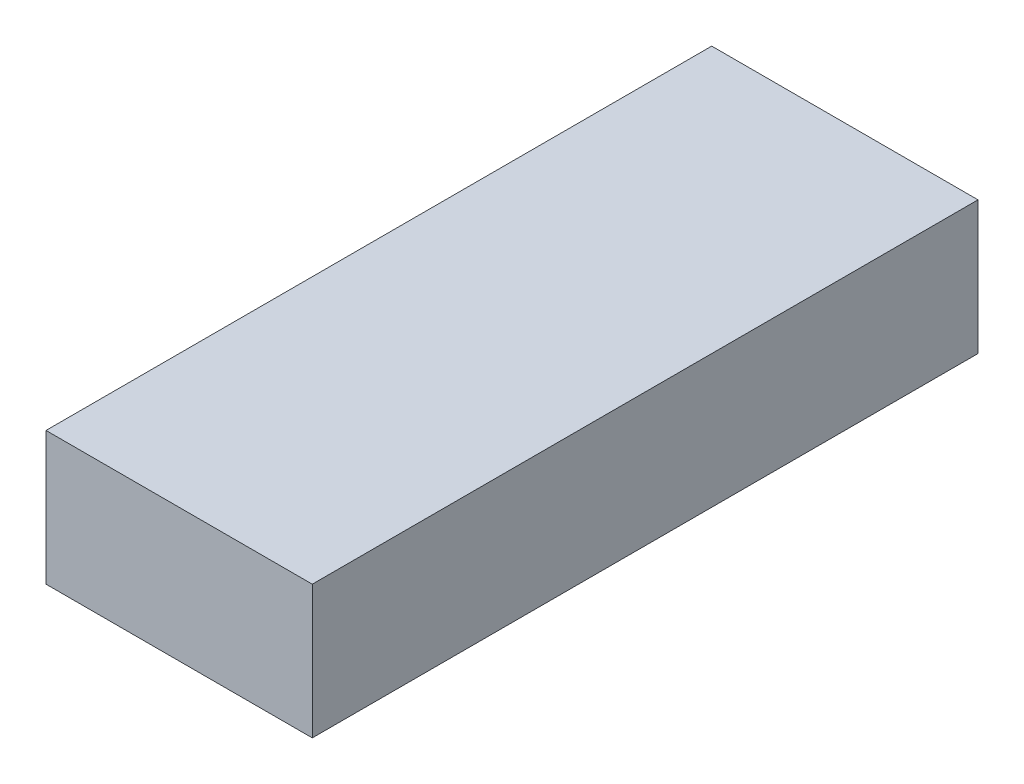
SolidWorks part; units mm, degrees
ref_plane "Front Plane" through (0, 0, 0) normal (0, 0, 1) x (1, 0, 0)
ref_plane "Top Plane" through (0, 0, 0) normal (0, 1, 0) x (1, 0, 0)
ref_plane "Right Plane" through (0, 0, 0) normal (1, 0, 0) x (0, 0, -1)
sketch "Sketch1" plane through (0, 0, 0) normal (0, 0, 1) x (1, 0, 0)
  line L1 (3, -1.5) -> (-3, -1.5)
  line L2 (3, -1.5) -> (3, 1.5)
  line L3 (3, 1.5) -> (-3, 1.5)
  line L4 (-3, -1.5) -> (-3, 1.5)
  line L5 (0, 1.5) -> (0, -1.5) construction
  line L6 (3, 0) -> (-3, 0) construction
  point P0 (0, 0)
  dimension "D1" = 3
  dimension "D2" = 6
extrude "Boss-Extrude1" add sketch "Sketch1" along normal mid plane 15
